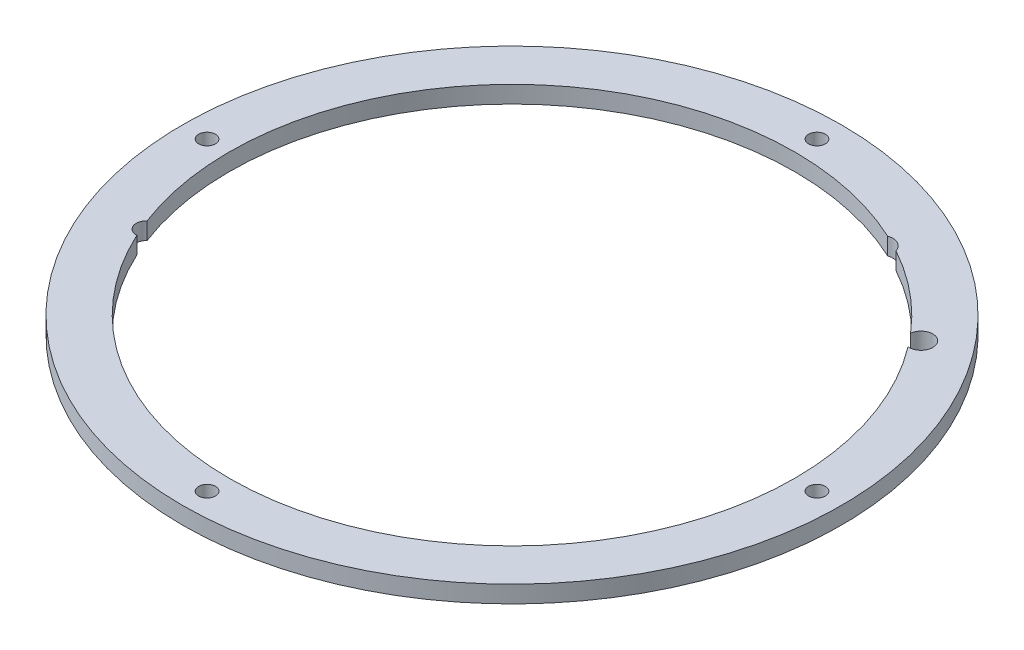
SolidWorks part; units mm, degrees
material "ABS"
ref_plane "前视基准面" through (0, 0, 0) normal (0, 0, 1) x (1, 0, 0)
ref_plane "上视基准面" through (0, 0, 0) normal (0, 1, 0) x (1, 0, 0)
ref_plane "右视基准面" through (0, 0, 0) normal (1, 0, 0) x (0, 0, -1)
other "Configuration Table"
sketch "草图1" plane through (0, 0, 0) normal (0, 1, 0) x (1, 0, 0)
  circle A0 centre (0, 0) radius 87.5
  circle A1 centre (0, 0) radius 102
  circle A2 centre (0, 94.385) radius 2.6
  circle A3 centre (0, 0) radius 94.385 construction
  circle A4 centre (94.385, 0) radius 2.6
  circle A5 centre (0, -94.385) radius 2.6
  circle A6 centre (-94.385, 0) radius 2.6
  dimension "D1" = 204
  dimension "D2" = 175
  dimension "D3" = 5.2
  dimension "D5" = 188.77
  dimension "D4" = 4
extrude "凸台-拉伸1" add sketch "草图1" along normal blind 5.3
sketch "草图2" plane through (0, 0, 0) normal (0, -1, 0) x (1, 0, 0)
  line L0 (0, 0) -> (94.385, 0) construction
  line L1 (0, 0) -> (70.1546, -56.4367) construction
  line L2 (0, 0) -> (72.1249, -72.1249) construction
  circle A0 centre (70.1546, -56.4367) radius 3.65
  circle A1 centre (0, 0) radius 102 construction
  circle A2 centre (-79.6202, 33.5169) radius 3.15
  circle A4 centre (38.3365, -75.5303) radius 4
  dimension "D1" = 7.3
  dimension "D3" = 6.3
  dimension "D4" = 8
  dimension "D2" = 45
extrude "切除-拉伸1" cut sketch "草图2" against normal through all
